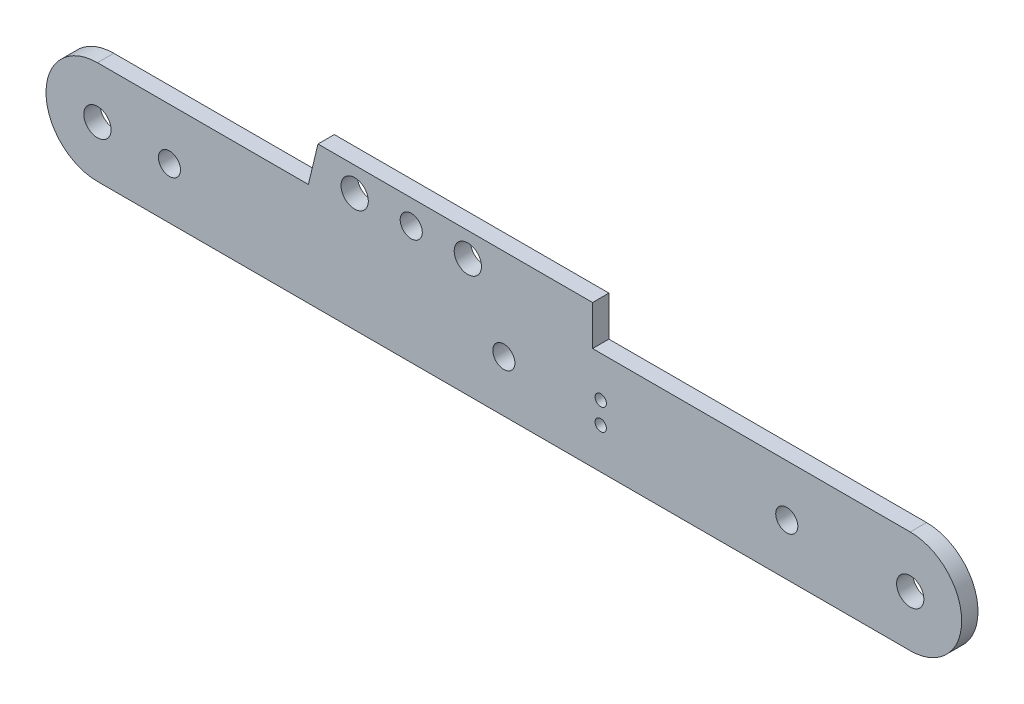
SolidWorks part; units mm, degrees
ref_plane "Front Plane" through (0, 0, 0) normal (0, 0, 1) x (1, 0, 0)
ref_plane "Top Plane" through (0, 0, 0) normal (0, 1, 0) x (1, 0, 0)
ref_plane "Right Plane" through (0, 0, 0) normal (1, 0, 0) x (0, 0, -1)
sketch "Sketch1" plane through (0, 0, 0) normal (0, 0, 1) x (1, 0, 0)
  line L1 (-79, 10) -> (79, 10)
  line L2 (-79, 10) -> (-79, -10) construction
  line L3 (-79, -10) -> (79, -10)
  line L4 (79, 10) -> (79, -10) construction
  line L5 (0, -10) -> (0, 10) construction
  line L6 (-79, 0) -> (79, 0) construction
  arc A0 (-79, -10) -> (-79, 10) centre (-79, 0) cw
  arc A1 (79, 10) -> (79, -10) centre (79, 0) cw
  point P0 (0, 0)
  dimension "D1" = 158
  dimension "D2" = 20
extrude "Boss-Extrude1" add sketch "Sketch1" along normal blind 3.175
hole_wizard "M5 Clearance Hole1" positions "Sketch5" profile "Sketch6" hole size "M5" standard "ANSI Metric" end condition through all
sketch "Sketch5" plane through (0, 0, 0) normal (0, 0, -1) x (-1, 0, 0)
  point P0 (-79, 0)
  point P3 (79, 0)
sketch "Sketch6" plane through (79, 0, 0) normal (1, 0, 0) x (0, 1, 0)
  line L0 (0, 0) -> (0, 3.175)
  line L1 (0, 3.175) -> (2.65, 3.175)
  line L2 (2.65, 3.175) -> (2.65, 0)
  line L5 (2.65, 0) -> (0, 0)
  line L11 (0, -6.35) -> (0, 107.95) construction
  dimension "Thru Hole Dia." = 5.3
  dimension "Thru Hole Depth" = 3.175
sketch "Sketch7" plane through (0, 0, 0) normal (0, 0, -1) x (-1, 0, 0)
  line L0 (-79, 6.5) -> (7, 6.5) construction
  line L1 (7, 13) -> (29, 13) construction
  line L2 (18, 13) -> (18, 32) construction
  line L4 (-17.25, 46.25) -> (29.25, 46.25)
  line L5 (-17.25, 46.25) -> (-17.25, 17.75)
  line L6 (-17.25, 17.75) -> (29.25, 17.75)
  line L7 (29.25, 46.25) -> (29.25, 17.75)
  line L8 (6, 17.75) -> (6, 46.25) construction
  line L9 (-17.25, 32) -> (29.25, 32) construction
  circle A0 centre (18, 32) radius 12.5
  circle A1 centre (7, 13) radius 7.5
  circle A2 centre (-79, 0) radius 6.5
  circle A3 centre (7, 13) radius 6.5
  circle A4 centre (29, 13) radius 7.5
  circle A5 centre (29, 13) radius 6.5
  circle A6 centre (7, 13) radius 3.5
  point P44 (6, 32)
  dimension "D1" = 25
  dimension "D2" = 15
  dimension "D3" = 13
  dimension "D9" = 7
  dimension "D4" = 18
  dimension "D5" = 32
  dimension "D6" = 11.25
  dimension "D7" = 46.5
  dimension "D8" = 28.5
  dimension "D10" = 22
sketch "Sketch8" plane through (0, 0, 0) normal (0, 0, -1) x (-1, 0, 0)
  line L1 (38, 10) -> (36.1293, 17.75)
  line L3 (36.1293, 17.75) -> (-17.25, 17.75)
  line L7 (-17.25, 17.75) -> (-17.25, 10)
  line L9 (-17.25, 10) -> (38, 10)
  line L13 (0, 99.6228) -> (0, 118.0196) construction
  line L14 (0, 0) -> (0, 46.25) construction
  line L15 (29.25, 46.25) -> (7.25, 46.25) construction
  line L16 (7.25, 46.25) -> (-2, 10) construction
  line L17 (-79, 10) -> (79, 10) construction
  line L18 (-2, 10) -> (38, 10) construction
  line L19 (38, 10) -> (29.25, 46.25) construction
  line L20 (-17.25, 46.25) -> (29.25, 46.25) construction
  line L21 (18, 32) -> (18, 10) construction
  dimension "D1" = 22
  dimension "D2" = 40
extrude "Boss-Extrude2" add sketch "Sketch8" against normal up to surface (3.175 mm away) up to face at (76.35, 0, 3.175)
hole_wizard "M5 Clearance Hole2" positions "Sketch9" profile "Sketch10" hole size "M5" standard "ANSI Metric" end condition through all
sketch "Sketch9" plane through (0, 0, 0) normal (0, 0, -1) x (-1, 0, 0)
  point P0 (7, 13)
  point P3 (29, 13)
sketch "Sketch10" plane through (-7, 13, 0) normal (1, 0, 0) x (0, 1, 0)
  line L0 (0, 0) -> (0, 3.175)
  line L1 (0, 3.175) -> (2.65, 3.175)
  line L2 (2.65, 3.175) -> (2.65, 0)
  line L5 (2.65, 0) -> (0, 0)
  line L11 (0, -6.35) -> (0, 107.95) construction
  dimension "Thru Hole Dia." = 5.3
  dimension "Thru Hole Depth" = 3.175
hole_wizard "M4 Clearance Hole1" positions "Sketch14" profile "Sketch15" hole size "M4" standard "ANSI Metric" end condition through all
sketch "Sketch14" plane through (0, 0, 0) normal (0, 0, -1) x (-1, 0, 0)
  line L0 (0, 0) -> (-55, 0) construction
  line L2 (0, 0) -> (65, 0) construction
  point P5 (-55, 0)
  point P14 (18, 13)
  point P22 (65, 0)
  point P32 (0, 0)
  dimension "D2" = 55
  dimension "D3" = 65
sketch "Sketch15" plane through (0, 0, 0) normal (1, 0, 0) x (0, 1, 0)
  line L0 (0, 0) -> (0, 3.175)
  line L1 (0, 3.175) -> (2.15, 3.175)
  line L2 (2.15, 3.175) -> (2.15, 0)
  line L5 (2.15, 0) -> (0, 0)
  line L11 (0, -6.35) -> (0, 107.95) construction
  dimension "Thru Hole Dia." = 4.3
  dimension "Thru Hole Depth" = 3.175
hole_wizard "M2 Clearance Hole1" positions "Sketch16" profile "Sketch17" hole size "M2" standard "ANSI Metric" end condition through all
sketch "Sketch16" plane through (0, 0, 0) normal (0, 0, -1) x (-1, 0, 0)
  line L0 (0, 0) -> (-18.8375, 0) construction
  line L1 (-18.8375, 0) -> (-18.8375, 2.1) construction
  line L2 (-17.25, 17.75) -> (-17.25, 10) construction
  point P5 (-18.8375, 2.1)
  point P11 (-18.8375, -2.1)
  dimension "D1" = 1.5875
  dimension "D2" = 2.1
sketch "Sketch17" plane through (18.8375, -2.1, 0) normal (1, 0, 0) x (0, 1, 0)
  line L0 (0, 0) -> (0, 3.175)
  line L1 (0, 3.175) -> (1.1, 3.175)
  line L2 (1.1, 3.175) -> (1.1, 0)
  line L5 (1.1, 0) -> (0, 0)
  line L11 (0, -6.35) -> (0, 107.95) construction
  dimension "Thru Hole Dia." = 2.2
  dimension "Thru Hole Depth" = 3.175
